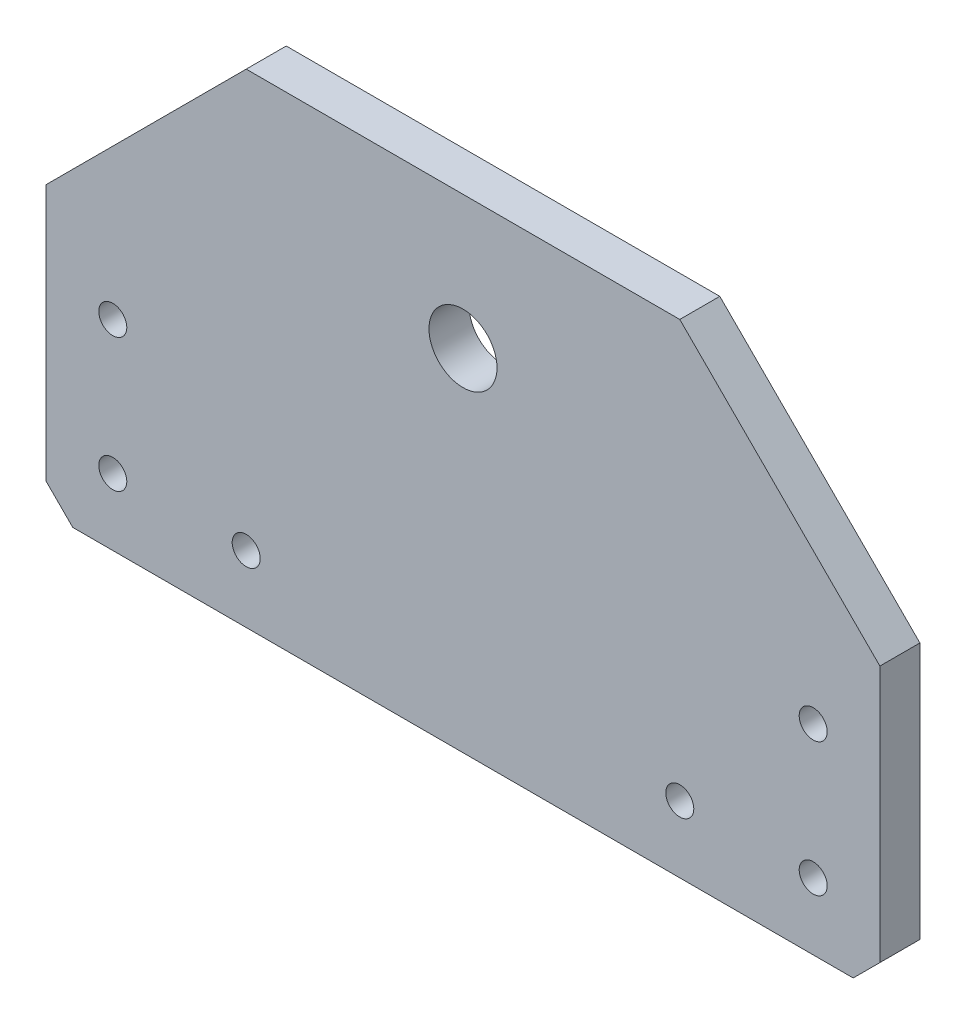
SolidWorks part; units mm, degrees
ref_plane "前视基准面" through (0, 0, 0) normal (0, 0, 1) x (1, 0, 0)
ref_plane "上视基准面" through (0, 0, 0) normal (0, 1, 0) x (1, 0, 0)
ref_plane "右视基准面" through (0, 0, 0) normal (1, 0, 0) x (0, 0, -1)
sketch "草图1" plane through (0, 0, 0) normal (0, 0, 1) x (1, 0, 0)
  line L0 (-32.5, -42.5) -> (32.5, -42.5) construction
  line L1 (-52.5, -42.5) -> (-32.5, -42.5) construction
  line L2 (32.5, -42.5) -> (52.5, -42.5) construction
  line L3 (-62.5, 20) -> (-62.5, -52.5)
  line L4 (-62.5, -52.5) -> (62.5, -52.5)
  line L5 (62.5, -52.5) -> (62.5, 20)
  line L6 (62.5, 20) -> (-62.5, 20)
  circle A0 centre (0, 0) radius 5.1
  circle A1 centre (-32.5, -42.5) radius 2.1
  circle A2 centre (32.5, -42.5) radius 2.1
  circle A3 centre (-52.5, -42.5) radius 2.1
  circle A4 centre (52.5, -42.5) radius 2.1
  circle A5 centre (-52.5, -22.5) radius 2.1
  circle A6 centre (52.5, -22.5) radius 2.1
  point P7 (0, -42.5)
  dimension "D1" = 10.2
  dimension "D2" = 42.5
  dimension "D3" = 4.2
  dimension "D5" = 20
  dimension "D6" = 105
  dimension "D9" = 10
  dimension "D4" = 105
  dimension "D11" = 20
  dimension "D7" = 20
  dimension "D8" = 10
  dimension "D10" = 10
extrude "凸台-拉伸1" add sketch "草图1" along normal mid plane 6
chamfer "倒角1" distance 30 angle 45 2 edges at (-62.5, 20, 0) (62.5, 20, 0)
chamfer "倒角2" distance 4 angle 45 2 edges at (-62.5, -52.5, 0) (62.5, -52.5, 0)
chamfer "倒角3" distance 2 angle 45 4 edges at (54.6, -42.5, -3) (54.6, -22.5, -3) (-50.4, -42.5, -3) (-50.4, -22.5, -3)
